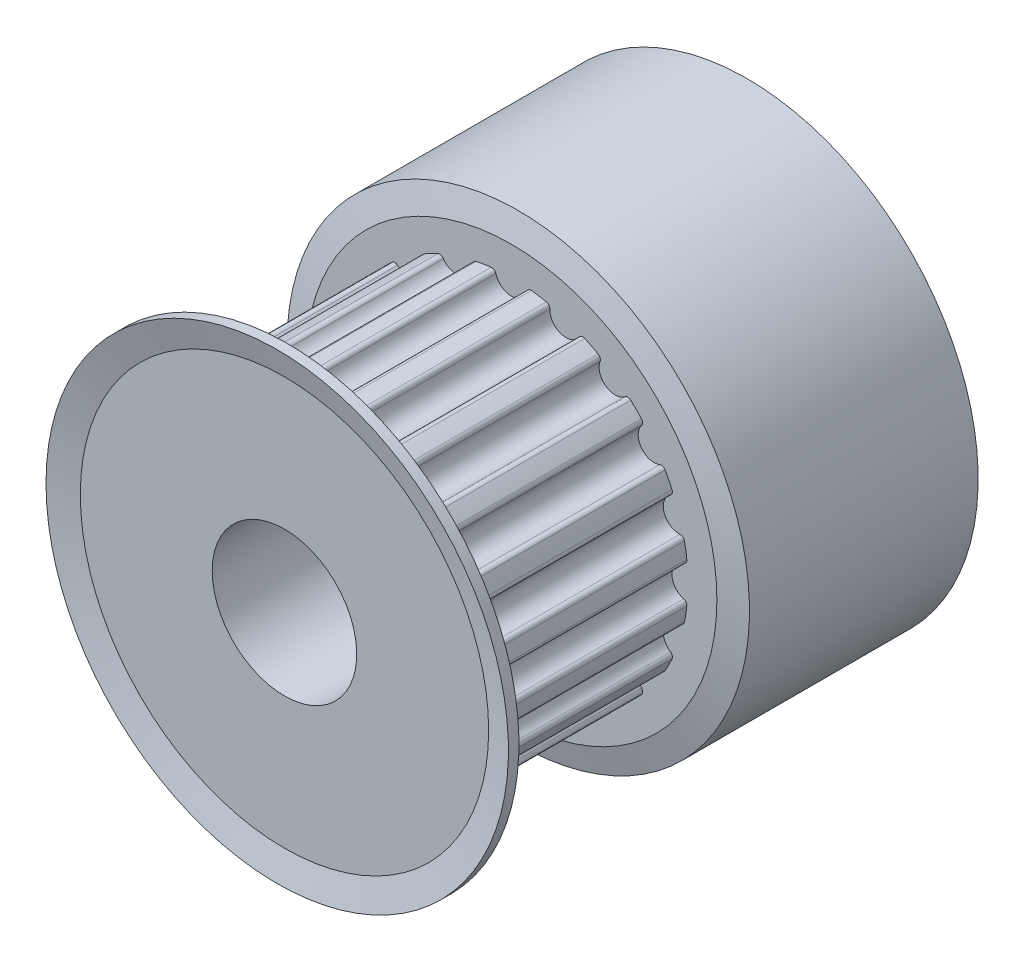
SolidWorks part; units mm, degrees
material "2024-T4"
ref_plane "Front Plane" through (0, 0, 0) normal (0, 0, 1) x (1, 0, 0)
ref_plane "Top Plane" through (0, 0, 0) normal (0, 1, 0) x (1, 0, 0)
ref_plane "Right Plane" through (0, 0, 0) normal (1, 0, 0) x (0, 0, -1)
sketch "Sketch1" plane through (0, 0, 0) normal (1, 0, 0) x (0, 0, -1)
  line L0 (0, 0) -> (-16, 0) construction
  line L1 (-16, 0) -> (-16, -2.5) construction
  line L2 (-16, -2.5) -> (0, -2.5) construction
  line L3 (0, -2.5) -> (0, 0) construction
  line L4 (0, -2.5) -> (0, -8)
  line L5 (0, -8) -> (-7.9115, -8)
  line L6 (-8.15, -7.11) -> (-8.15, -6.11)
  line L7 (-8.15, -6.11) -> (-15.65, -6.11)
  line L8 (-16, -2.5) -> (-16, -6.11)
  line L9 (-15.65, -6.11) -> (-15.65, -7.11)
  line L10 (-15.65, -7.11) -> (-15.8885, -8)
  line L11 (-16, -6.11) -> (-16, -7.0639)
  line L12 (-16, -7.0639) -> (-16.2508, -8)
  line L13 (-15.8885, -8) -> (-16.2508, -8)
  line L14 (-16, -7.0639) -> (-16.2265, -7.9094) construction
  line L15 (-11.9, -6.11) -> (-11.9, -9.189) construction
  line L16 (-8.15, -7.11) -> (-7.9115, -8)
  line L17 (-16, -2.5) -> (0, -2.5)
  dimension "D1" = 16
  dimension "D2" = 2.5
  dimension "D3" = 8
  dimension "D4" = 8.15
  dimension "D5" = 6.11
  dimension "D6" = 1
  dimension "D7" = 15
  dimension "D8" = 0.35
  dimension "D9" = 0.35
revolve "Revolve1" add sketch "Sketch1" angle 360 about L0
sketch "Sketch2" plane through (0, 0, 8.15) normal (0, 0, 1) x (1, 0, 0)
  circle A0 centre (0, 0) radius 6.11 construction
  circle A1 centre (0, 0) radius 6.11 construction
  circle A2 centre (0, 6.11) radius 0.555
  circle A3 centre (1.8881, 5.811) radius 0.555
  circle A4 centre (3.5914, 4.9431) radius 0.555
  circle A5 centre (4.9431, 3.5914) radius 0.555
  circle A6 centre (5.811, 1.8881) radius 0.555
  circle A7 centre (6.11, 0) radius 0.555
  circle A8 centre (5.811, -1.8881) radius 0.555
  circle A9 centre (4.9431, -3.5914) radius 0.555
  circle A10 centre (3.5914, -4.9431) radius 0.555
  circle A11 centre (1.8881, -5.811) radius 0.555
  circle A12 centre (0, -6.11) radius 0.555
  circle A13 centre (-1.8881, -5.811) radius 0.555
  circle A14 centre (-3.5914, -4.9431) radius 0.555
  circle A15 centre (-4.9431, -3.5914) radius 0.555
  circle A16 centre (-5.811, -1.8881) radius 0.555
  circle A17 centre (-6.11, 0) radius 0.555
  circle A18 centre (-5.811, 1.8881) radius 0.555
  circle A19 centre (-4.9431, 3.5914) radius 0.555
  circle A20 centre (-3.5914, 4.9431) radius 0.555
  circle A21 centre (-1.8881, 5.811) radius 0.555
  point P45 (0, 0)
  dimension "D1" = 1.11
  dimension "D2" = 20
extrude "Cut-Extrude1" cut sketch "Sketch2" along normal blind 7.5
fillet "Fillet1" radius 0.15 40 edges at (5.6157, 2.4076, 11.9) (5.9583, 1.353, 11.9) (6.0848, 0.5544, 11.9) (6.0848, -0.5544, 11.9) (5.9583, -1.353, 11.9) (5.6157, -2.4076, 11.9) (5.2486, -3.128, 11.9) (4.5968, -4.0251, 11.9) (4.0251, -4.5968, 11.9) (3.128, -5.2486, 11.9) (2.4076, -5.6157, 11.9) (1.353, -5.9583, 11.9) (0.5544, -6.0848, 11.9) (-0.5544, -6.0848, 11.9) (4.5968, 4.0251, 11.9) (5.2486, 3.128, 11.9) (3.128, 5.2486, 11.9) (4.0251, 4.5968, 11.9) (1.353, 5.9583, 11.9) (2.4076, 5.6157, 11.9) (-0.5544, 6.0848, 11.9) (0.5544, 6.0848, 11.9) (-2.4076, 5.6157, 11.9) (-1.353, 5.9583, 11.9) (-4.0251, 4.5968, 11.9) (-3.128, 5.2486, 11.9) (-1.353, -5.9583, 11.9) (-2.4076, -5.6157, 11.9) (-3.128, -5.2486, 11.9) (-4.0251, -4.5968, 11.9) (-4.5968, -4.0251, 11.9) (-5.2486, -3.128, 11.9) (-5.6157, -2.4076, 11.9) (-5.9583, -1.353, 11.9) (-6.0848, -0.5544, 11.9) (-6.0848, 0.5544, 11.9) (-5.9583, 1.353, 11.9) (-5.6157, 2.4076, 11.9) (-5.2486, 3.128, 11.9) (-4.5968, 4.0251, 11.9)
